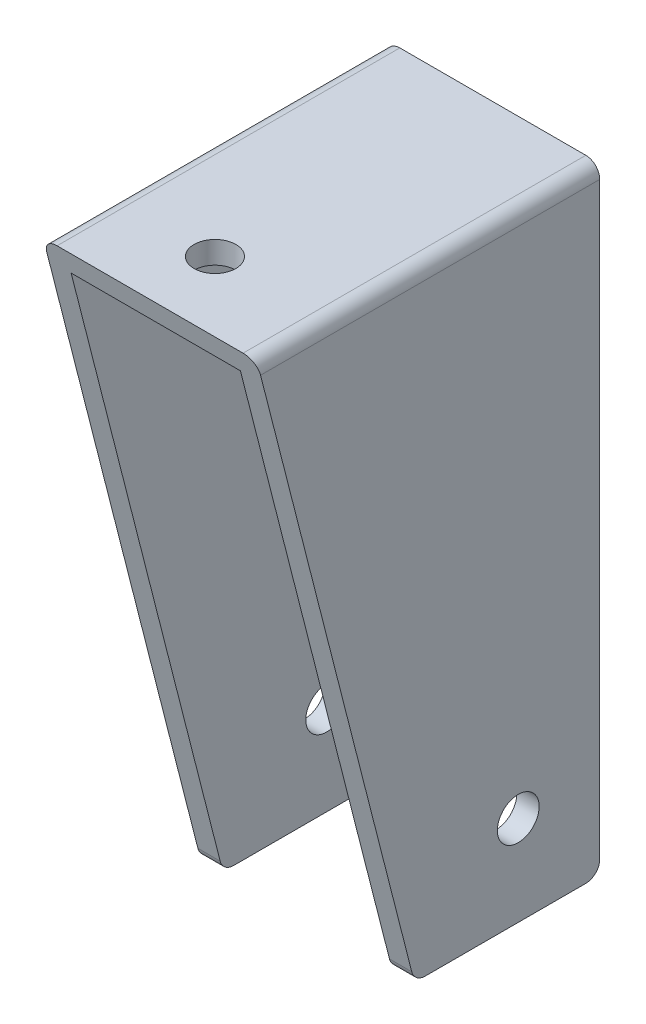
SolidWorks part; units mm, degrees
ref_plane "Plan de face" through (0, 0, 0) normal (0, 0, 1) x (1, 0, 0)
ref_plane "Plan de dessus" through (0, 0, 0) normal (0, 1, 0) x (1, 0, 0)
ref_plane "Plan de droite" through (0, 0, 0) normal (1, 0, 0) x (0, 0, -1)
sketch "Esquisse1" plane through (0, 0, 0) normal (1, 0, 0) x (0, 0, -1)
  line L0 (0, 0) -> (0, 44.26)
  line L1 (0, 44.26) -> (-24.6, 44.26)
  line L2 (-24.6, 44.26) -> (-13.3, 0)
  line L3 (-13.3, 0) -> (0, 0)
  dimension "D1" = 44.26
  dimension "D2" = 24.6
  dimension "D3" = 13.3
extrude "Boss.-Extru.1" add sketch "Esquisse1" along normal blind 15.35
sketch "Esquisse2" plane through (0, 0, 0) normal (0, 0, -1) x (-1, 0, 0)
  line L0 (-15.35, 44.26) -> (0, 44.26) construction
  line L1 (-15.35, 0) -> (0, 0) construction
  line L2 (-13.75, 0) -> (-13.75, 42.66)
  line L4 (-13.75, 42.66) -> (-1.6, 42.66)
  line L5 (-1.6, 42.66) -> (-1.6, 0)
  line L6 (-1.6, 0) -> (-13.75, 0)
  line L7 (0, 0) -> (0, 44.26) construction
  line L8 (-15.35, 0) -> (-15.35, 44.26) construction
  point P4 (0, 0)
  dimension "D1" = 1.6
  dimension "D2" = 1.6
  dimension "D3" = 1.6
extrude "Enlèv. mat.-Extru.1" cut sketch "Esquisse2" against normal through all
fillet "Congé1" radius 1 6 edges at (15.35, 44.26, 12.3) (0, 44.26, 12.3) (0.8, 0, 13.3) (14.55, 0, 13.3) (0.8, 0, 0) (14.55, 0, 0)
sketch "Esquisse3" plane through (0, 0, 0) normal (-1, 0, 0) x (0, 0, 1)
  line L0 (12.5232, 0) -> (1, 0) construction
  line L1 (0, 1) -> (0, 43.26) construction
  circle A0 centre (5.85, 6.46) radius 1.5
  dimension "D1" = 3
  dimension "D2" = 6.46
  dimension "D3" = 5.85
extrude "Enlèv. mat.-Extru.2" cut sketch "Esquisse3" against normal through all
sketch "Esquisse4" plane through (0, 44.26, 0) normal (0, 1, 0) x (1, 0, 0)
  line L0 (14.35, -24.6) -> (1, -24.6) construction
  circle A0 centre (7.3315, -19.6) radius 1.5
  dimension "D1" = 3
  dimension "D2" = 5
extrude "Enlèv. mat.-Extru.3" cut sketch "Esquisse4" against normal through all
